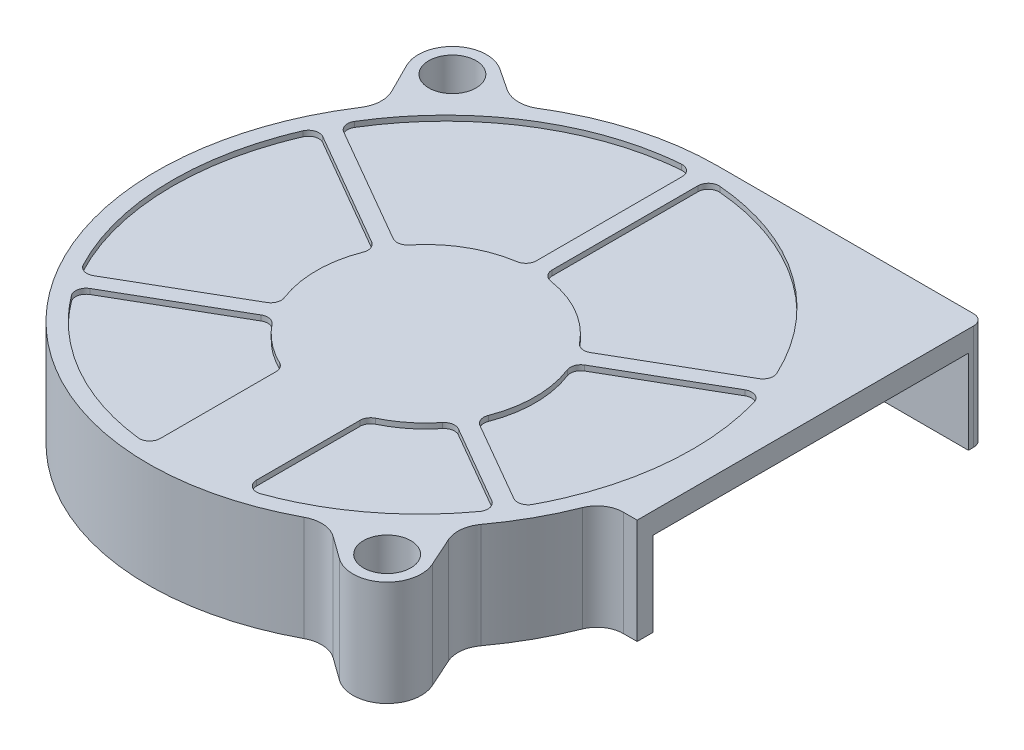
SolidWorks part; units mm, degrees
ref_plane "Front Plane" through (0, 0, 0) normal (0, 0, 1) x (1, 0, 0)
ref_plane "Top Plane" through (0, 0, 0) normal (0, 1, 0) x (1, 0, 0)
ref_plane "Right Plane" through (0, 0, 0) normal (1, 0, 0) x (0, 0, -1)
ref_plane "Plane1" through (-0.9289, 0, -30.9104) normal (0.03, 0, 0.9995) x (0, 1, 0)
sketch "Sketch18" plane through (0, 0, 0) normal (0, 1, 0) x (1, 0, 0)
  line L0 (-23.0057, 21.1739) -> (-21.5825, 18.3332)
  line L1 (14.4232, -22.6366) -> (12.2821, -21.0936)
  line L2 (-18.3115, 25.3434) -> (-16.2051, 23.9551)
  line L3 (-16.9421, 19.0744) -> (0, 0) construction
  line L4 (16.3234, -20) -> (0, 0) construction
  line L5 (-33.0815, -23.9) -> (4.114, -23.9) construction
  line L6 (-26.2, -10.7544) -> (-26.2, -0.8211) construction
  line L7 (0, 0) -> (0, -6.8242) construction
  line L8 (-4, 0) -> (-4, -27.6209) construction
  line L9 (4, 0) -> (4, -27.6209) construction
  line L10 (0, 0) -> (0, 25.466) construction
  line L11 (0.75, 0) -> (0.75, 25.466) construction
  line L12 (-0.75, 0) -> (-0.75, 25.466) construction
  line L13 (-12.8119, -19.8447) -> (10.3119, 23.6447) construction
  line L14 (-21.6522, 12.748) -> (19.1522, -8.948) construction
  line L15 (-1.25, 1.9) -> (3.3669, 1.9) construction
  line L16 (0, 0) -> (21.8429, 12.611) construction
  line L17 (0, 0) -> (-26.1434, 15.0939) construction
  line L18 (0, 0) -> (-23.531, -13.5856) construction
  line L19 (-0.0106, 27.7) -> (24.4, 27.7)
  line L20 (0, 0) -> (22.2135, -12.825) construction
  line L21 (0, 0) -> (6.1332, 0) construction
  line L22 (4, 0) -> (4, -6.8242) construction
  line L23 (-4, 0) -> (-4, -6.8242) construction
  line L24 (-1.5, 0) -> (-26.5184, 14.4444) construction
  line L25 (-1.5, 0) -> (-23.906, -12.9361) construction
  line L26 (25.4, 26.7) -> (25.4, -5.3)
  line L27 (25.4, -5.3) -> (22.3333, -5.3)
  line L28 (1.5, 0) -> (-25.7684, 15.7434) construction
  line L29 (1.5, 0) -> (-23.156, -14.2351) construction
  line L30 (9.3582, -4.5369) -> (22.5885, -12.1755) construction
  line L31 (19.2873, -18.6667) -> (18.0311, -15.874)
  line L157 (8.6082, -5.836) -> (21.8385, -13.4745) construction
  line L159 (9.3582, 4.5369) -> (22.2179, 11.9615) construction
  line L161 (8.6082, 5.836) -> (21.4679, 13.2605) construction
  line L164 (11.0633, 27.6622) -> (11.0633, 28.1486) construction
  line L165 (18.2349, 28.1486) -> (18.2349, 27.6622) construction
  line L166 (16.3586, 27.6622) -> (16.3586, 28.1486) construction
  line L167 (12.9535, 27.6622) -> (12.9535, 28.1486) construction
  line L168 (11.0633, 28.1486) -> (18.2349, 28.1486) construction
  line L169 (-26.0052, -3.975) -> (-26.3506, -3.975) construction
  line L170 (-26.3506, 3.1828) -> (-25.7716, 3.1828) construction
  line L171 (-26.1178, 1.3065) -> (-26.3506, 1.3065) construction
  line L172 (-26.0193, -2.0987) -> (-26.3506, -2.0987) construction
  line L173 (-26.3506, -3.975) -> (-26.3506, 3.1828) construction
  line L174 (19.9063, -12.0569) -> (20.36, -12.2293) construction
  line L175 (22.6116, -6.1418) -> (22.2945, -6.0236) construction
  line L176 (21.4807, -7.7289) -> (21.9583, -7.9069) construction
  line L177 (20.6345, -10.3321) -> (21.0132, -10.4642) construction
  line L178 (20.36, -12.2293) -> (22.6116, -6.1418) construction
  circle A0 centre (16.3234, -20) radius 2.25
  arc A1 (19.2873, -18.6667) -> (14.4232, -22.6366) centre (16.3234, -20) ccw construction
  circle A2 centre (-20.1, 22.6298) radius 2.25
  arc A3 (-18.3115, 25.3434) -> (-23.0057, 21.1739) centre (-20.1, 22.6298) ccw
  circle A4 centre (0, 0) radius 9.2 construction
  arc A5 (-16.2051, 23.9551) -> (-13.1979, 23.9077) centre (-14.6643, 26.293) ccw
  arc A6 (-21.5825, 18.3332) -> (-21.7386, 15.5524) centre (-24.0858, 17.079) cw
  arc A7 (-23.0057, 21.1739) -> (-18.3115, 25.3434) centre (-20.1, 22.6298) ccw construction
  arc A8 (12.2821, -21.0936) -> (9.3249, -20.8959) centre (10.6451, -23.3651) ccw
  arc A9 (25.4, 26.7) -> (24.4, 27.7) centre (24.4, 26.7) ccw
  circle A10 centre (0, 0) radius 10.4 construction
  arc A11 (18.0311, -15.874) -> (18.3294, -13.0658) centre (20.5846, -14.7253) cw
  arc A12 (14.4232, -22.6366) -> (19.2873, -18.6667) centre (16.3234, -20) ccw
  ellipse E0 centre (-1.25, 1.9) end of major axis (10.3119, 23.6447) minor radius 23.1069 construction
  ellipse E1 centre (-1.25, 1.9) end of major axis (-13.5161, -21.1691) minor radius 24.6069 (-21.7386, 15.5524) -> (9.3249, -20.8959) ccw
  ellipse E2 centre (-1.25, 1.9) end of major axis (-13.5161, -21.1691) minor radius 24.6069 (-0.0106, 27.7) -> (-13.1979, 23.9077) ccw
  ellipse E3 centre (-1.25, 1.9) end of major axis (-13.5161, -21.1691) minor radius 24.6069 (22.3333, -5.3) -> (-0.0106, 27.7) ccw construction
  ellipse E4 centre (-1.25, 1.9) end of major axis (-13.5161, -21.1691) minor radius 24.6069 (18.3294, -13.0658) -> (22.3333, -5.3) ccw
  dimension "D1" = 6.5
  dimension "D2" = 4.5
  dimension "D5" = 2.8
  dimension "D7" = 0.75
  dimension "D8" = 1
  dimension "D16" = 18.4
  dimension "D34" = 15
  dimension "D6" = 15
  dimension "D9" = 16.3234
  dimension "D10" = 20.1
  dimension "D11" = 25.4
  dimension "D12" = 27.7
  dimension "D13" = 51.6
  dimension "D14" = 20
  dimension "D15" = 51.6
  dimension "D21" = 32
  dimension "D22" = 28
  dimension "D23" = 0.75
  dimension "D24" = 1.9
  dimension "D25" = 1.25
  dimension "D26" = 1.5
  dimension "D27" = 1.5
  dimension "D28" = 30
  dimension "D29" = 30
  dimension "D30" = 30
  dimension "D31" = 30
  dimension "D33" = 48.388
  dimension "D17" = 4
  dimension "D18" = 4
  dimension "D19" = 1.2
  dimension "D20" = 0.75
  dimension "D32" = 0.75
extrude "Boss-Extrude3" add sketch "Sketch18" along normal blind 2 separate body
sketch "Sketch21" plane through (0, 2, 0) normal (0, -1, 0) x (1, 0, 0)
  line L2 (1.5, 0) -> (-23.156, 14.2351) construction
  line L3 (-1.5, 0) -> (-23.906, 12.9361) construction
  line L4 (8.6082, 5.836) -> (21.8385, 13.4745) construction
  line L5 (9.3582, 4.5369) -> (22.5885, 12.1755) construction
  line L6 (9.3807, 6.282) -> (16.8897, 10.6173)
  line L7 (10.1307, 4.9829) -> (17.7495, 9.3817)
  line L11 (1.5, 0) -> (-25.7684, -15.7434) construction
  line L13 (4, 0) -> (4, 27.6209) construction
  line L14 (-0.75, 0) -> (-0.75, -25.466) construction
  line L15 (4, 10.245) -> (4, 20.0877)
  line L16 (-1.5, 0) -> (-26.5184, -14.4444) construction
  line L18 (-10.1307, -4.9829) -> (-21.1393, -11.3387)
  line L19 (0.75, 0) -> (0.75, -25.466) construction
  line L20 (8.6082, -5.836) -> (21.4679, -13.2605) construction
  line L21 (9.3582, -4.5369) -> (22.2179, -11.9615) construction
  line L22 (9.3807, -6.282) -> (19.5418, -12.1485)
  line L23 (10.1307, -4.9829) -> (19.789, -10.5592)
  line L24 (-4, 10.245) -> (-4, 21.2528)
  line L25 (-9.3807, 6.282) -> (-19.697, 12.2381)
  line L26 (-10.1307, 4.9829) -> (-20.5768, 11.014)
  line L27 (-9.3807, -6.282) -> (-20.5254, -12.7164)
  line L28 (-0.75, -11.2649) -> (-0.75, -25.1306)
  line L29 (0.75, -11.2649) -> (0.75, -25.1281)
  line L30 (-4, 0) -> (-4, 27.6209) construction
  circle A0 centre (0, 0) radius 10.4 construction
  arc A1 (-4.5614, 9.3463) -> (-8.1017, 6.521) centre (0, 0) ccw
  arc A2 (8.1017, 6.521) -> (4.5614, 9.3463) centre (0, 0) ccw
  arc A3 (9.6982, -3.7558) -> (9.6982, 3.7558) centre (0, 0) ccw
  arc A4 (1.5965, -10.2767) -> (8.1017, -6.521) centre (0, 0) ccw
  arc A5 (-9.6982, 3.7558) -> (-9.6982, -3.7558) centre (0, 0) ccw
  arc A6 (-8.1017, -6.521) -> (-1.5965, -10.2767) centre (0, 0) ccw
  arc A9 (1.8322, -26.1247) -> (0.75, -25.1281) centre (1.75, -25.1281) cw
  arc A10 (-1.8301, -26.1274) -> (-0.75, -25.1306) centre (-1.75, -25.1306) ccw
  arc A11 (-0.75, -11.2649) -> (-1.5965, -10.2767) centre (-1.75, -11.2649) ccw
  arc A12 (0.75, -11.2649) -> (1.5965, -10.2767) centre (1.75, -11.2649) cw
  arc A13 (-20.8789, -14.1035) -> (-20.5254, -12.7164) centre (-20.0254, -13.5824) cw
  arc A14 (-9.3807, -6.282) -> (-8.1017, -6.521) centre (-8.8807, -7.148) cw
  arc A15 (19.5418, -12.1485) -> (19.9471, -13.4391) centre (19.0418, -13.0145) cw
  arc A16 (9.3807, -6.282) -> (8.1017, -6.521) centre (8.8807, -7.148) ccw
  arc A17 (19.789, -10.5592) -> (21.2499, -9.9702) centre (20.289, -9.6931) ccw
  arc A18 (10.1307, -4.9829) -> (9.6982, -3.7558) centre (10.6307, -4.1169) cw
  arc A19 (10.1307, 4.9829) -> (9.6982, 3.7558) centre (10.6307, 4.1169) ccw
  arc A20 (17.7495, 9.3817) -> (19.1317, 8.9866) centre (18.2495, 8.5156) cw
  arc A21 (16.8897, 10.6173) -> (17.1981, 12.0719) centre (16.3897, 11.4833) ccw
  arc A22 (9.3807, 6.282) -> (8.1017, 6.521) centre (8.8807, 7.148) cw
  arc A23 (4.5614, 9.3463) -> (4, 10.245) centre (5, 10.245) cw
  arc A24 (4, 20.0877) -> (5.3367, 21.0294) centre (5, 20.0877) cw
  arc A25 (-4, 21.2528) -> (-5.1175, 22.2459) centre (-5, 21.2528) ccw
  arc A26 (-4.5614, 9.3463) -> (-4, 10.245) centre (-5, 10.245) ccw
  arc A27 (-9.3807, 6.282) -> (-8.1017, 6.521) centre (-8.8807, 7.148) ccw
  arc A28 (-10.1307, 4.9829) -> (-9.6982, 3.7558) centre (-10.6307, 4.1169) cw
  arc A29 (-10.1307, -4.9829) -> (-9.6982, -3.7558) centre (-10.6307, -4.1169) ccw
  arc A30 (-21.1393, -11.3387) -> (-22.5567, -10.8706) centre (-21.6393, -10.4727) cw
  arc A31 (-21.9611, 10.6149) -> (-20.5768, 11.014) centre (-21.0768, 10.1479) cw
  arc A32 (-19.9944, 13.7074) -> (-19.697, 12.2381) centre (-19.197, 13.1041) ccw
  ellipse E0 centre (-1.25, -1.9) end of major axis (10.3119, -23.6447) minor radius 23.1069 construction
  ellipse E1 centre (-1.25, -1.9) end of major axis (10.3119, -23.6447) minor radius 23.1069 (-5.1175, 22.2459) -> (-19.9944, 13.7074) ccw
  ellipse E2 centre (-1.25, -1.9) end of major axis (10.3119, -23.6447) minor radius 23.1069 (17.1981, 12.0719) -> (5.3367, 21.0294) ccw
  ellipse E3 centre (-1.25, -1.9) end of major axis (10.3119, -23.6447) minor radius 23.1069 (21.2499, -9.9702) -> (19.1317, 8.9866) ccw
  ellipse E4 centre (-1.25, -1.9) end of major axis (10.3119, -23.6447) minor radius 23.1069 (1.8322, -26.1247) -> (19.9471, -13.4391) ccw
  ellipse E5 centre (-1.25, -1.9) end of major axis (10.3119, -23.6447) minor radius 23.1069 (-21.9611, 10.6149) -> (-22.5567, -10.8706) ccw
  ellipse E6 centre (-1.25, -1.9) end of major axis (10.3119, -23.6447) minor radius 23.1069 (-20.8789, -14.1035) -> (-1.8301, -26.1274) ccw
  point P84 (0.75, -10.3729)
  point P89 (-8.6082, -5.836)
  point P122 (-9.3582, 4.5369)
  point P125 (-9.3582, -4.5369)
  dimension "D1" = 1
extrude "Cut-Extrude9" cut sketch "Sketch21" along normal blind 0.5
fillet "Fillet4" radius 2.5 1 edges at (22.3333, 1, 5.3)
sketch "Sketch22" plane through (0, 0, 0) normal (0, 1, 0) x (1, 0, 0)
  line L0 (25.4, 26.2) -> (0.1345, 26.2)
  line L1 (24.0846, -3.8) -> (25.4, -3.8)
  line L2 (24.4, 26.2) -> (-0.0106, 26.2) construction
  line L3 (25.4, 26.2) -> (25.4, 26.7)
  line L7 (-16.2051, 23.9551) -> (-18.3115, 25.3434)
  line L8 (-23.0057, 21.1739) -> (-21.5825, 18.3332)
  line L9 (12.2821, -21.0936) -> (14.4232, -22.6366)
  line L10 (19.2873, -18.6667) -> (18.0311, -15.874)
  line L11 (24.0846, -5.3) -> (25.4, -5.3)
  line L12 (25.4, -5.3) -> (25.4, 26.7)
  line L13 (24.4, 27.7) -> (-0.0106, 27.7)
  line L14 (-16.2051, 23.9551) -> (-18.3115, 25.3434)
  line L15 (-23.0057, 21.1739) -> (-21.5825, 18.3332)
  line L16 (12.2821, -21.0936) -> (14.4232, -22.6366)
  line L17 (19.2873, -18.6667) -> (18.0311, -15.874)
  line L18 (24.0846, -5.3) -> (25.4, -5.3)
  line L19 (25.4, -5.3) -> (25.4, -3.8)
  line L20 (24.4, 27.7) -> (-0.0106, 27.7)
  circle A0 centre (16.3234, -20) radius 2.25 construction
  circle A1 centre (-20.1, 22.6298) radius 2.25 construction
  circle A2 centre (16.3234, -20) radius 2.25
  circle A3 centre (-20.1, 22.6298) radius 2.25
  arc A4 (24.0846, -3.8) -> (20.3734, -6.3078) centre (24.0846, -7.8) ccw
  arc A5 (24.0846, -3.8) -> (20.3675, -6.3226) centre (24.0846, -7.8) ccw construction
  arc A8 (-16.2051, 23.9551) -> (-13.1979, 23.9077) centre (-14.6643, 26.293) ccw
  arc A9 (-18.3115, 25.3434) -> (-23.0057, 21.1739) centre (-20.1, 22.6298) ccw
  arc A10 (-21.7386, 15.5524) -> (-21.5825, 18.3332) centre (-24.0858, 17.079) ccw
  arc A11 (12.2821, -21.0936) -> (9.3249, -20.8959) centre (10.6451, -23.3651) ccw
  arc A12 (14.4232, -22.6366) -> (19.2873, -18.6667) centre (16.3234, -20) ccw
  arc A13 (18.3294, -13.0658) -> (18.0311, -15.874) centre (20.5846, -14.7253) ccw
  arc A14 (24.0846, -5.3) -> (21.7614, -6.8766) centre (24.0846, -7.8) ccw
  arc A15 (25.4, 26.7) -> (24.4, 27.7) centre (24.4, 26.7) ccw
  arc A16 (-16.2051, 23.9551) -> (-13.1979, 23.9077) centre (-14.6643, 26.293) ccw
  arc A17 (-18.3115, 25.3434) -> (-23.0057, 21.1739) centre (-20.1, 22.6298) ccw
  arc A18 (-21.7386, 15.5524) -> (-21.5825, 18.3332) centre (-24.0858, 17.079) ccw
  arc A19 (12.2821, -21.0936) -> (9.3249, -20.8959) centre (10.6451, -23.3651) ccw
  arc A20 (14.4232, -22.6366) -> (19.2873, -18.6667) centre (16.3234, -20) ccw
  arc A21 (18.3294, -13.0658) -> (18.0311, -15.874) centre (20.5846, -14.7253) ccw
  arc A22 (24.0846, -5.3) -> (21.7614, -6.8766) centre (24.0846, -7.8) ccw
  arc A23 (25.4, 26.7) -> (24.4, 27.7) centre (24.4, 26.7) ccw
  ellipse E0 centre (-1.25, 1.9) end of major axis (10.3119, 23.6447) minor radius 23.1069 construction
  ellipse E1 centre (-1.25, 1.9) end of major axis (10.3119, 23.6447) minor radius 23.1069 (0.1345, 26.2) -> (20.3734, -6.3078) ccw
  ellipse E3 centre (-1.25, 1.9) end of major axis (-13.5161, -21.1691) minor radius 24.6069 (-0.0106, 27.7) -> (-13.1979, 23.9077) ccw
  ellipse E4 centre (-1.25, 1.9) end of major axis (-13.5161, -21.1691) minor radius 24.6069 (-21.7386, 15.5524) -> (9.3249, -20.8959) ccw
  ellipse E5 centre (-1.25, 1.9) end of major axis (-13.5161, -21.1691) minor radius 24.6069 (18.3294, -13.0658) -> (21.7614, -6.8766) ccw
  ellipse E6 centre (-1.25, 1.9) end of major axis (-13.5161, -21.1691) minor radius 24.6069 (-0.0106, 27.7) -> (-13.1979, 23.9077) ccw
  ellipse E7 centre (-1.25, 1.9) end of major axis (-13.5161, -21.1691) minor radius 24.6069 (-21.7386, 15.5524) -> (9.3249, -20.8959) ccw
  ellipse E8 centre (-1.25, 1.9) end of major axis (-13.5161, -21.1691) minor radius 24.6069 (18.3294, -13.0658) -> (21.7614, -6.8766) ccw
  dimension "D1" = 0
  dimension "D2" = 1.5
extrude "Boss-Extrude4" add sketch "Sketch22" against normal blind 8
